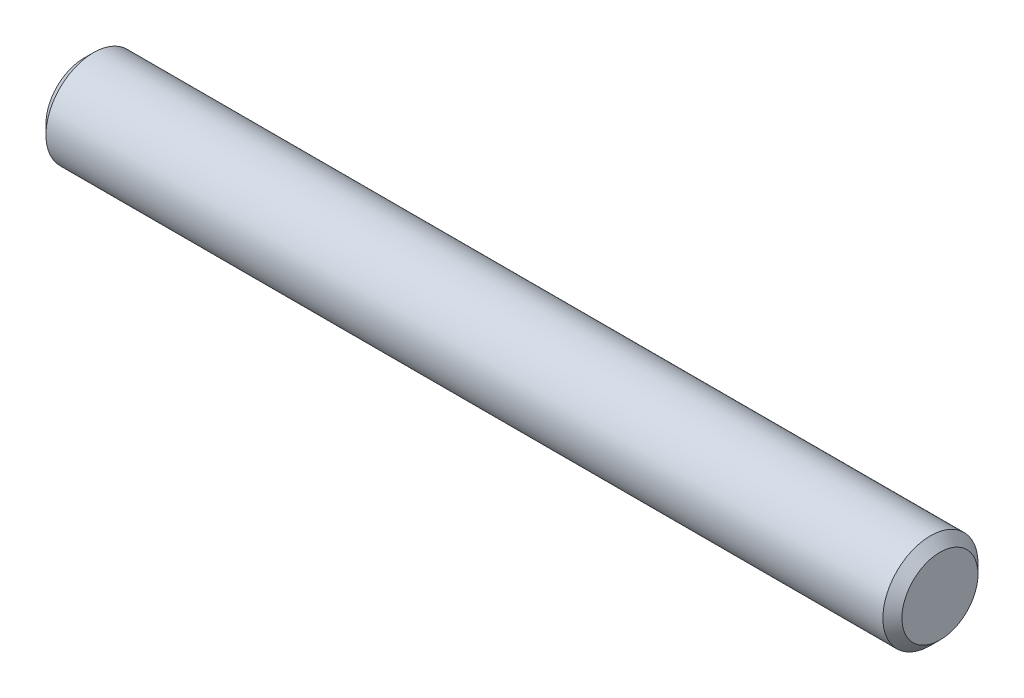
SolidWorks part; units mm, degrees
ref_plane "Front" through (0, 0, 0) normal (0, 0, 1) x (1, 0, 0)
ref_plane "Top" through (0, 0, 0) normal (0, 1, 0) x (1, 0, 0)
ref_plane "Right" through (0, 0, 0) normal (1, 0, 0) x (0, 0, -1)
sketch "Sketch1" plane through (0, 0, 0) normal (0, 0, 1) x (1, 0, 0)
  line L0 (-14.2875, 0) -> (14.2875, 0) construction
  line L1 (14.2875, 1.5875) -> (14.2875, -1.5875) construction
  line L2 (-14.2875, 1.5875) -> (-14.2875, -1.5875) construction
  dimension "Length" = 28.575
  dimension "Diameter" = 3.175
sketch "Sketch2" plane through (0, 0, 0) normal (1, 0, 0) x (0, 0, -1)
  circle A0 centre (0, 0) radius 1.5875
extrude "Extrude1" add sketch "Sketch2" against normal up to vertex (14.2875 mm away) and the other way up to vertex (14.2875 mm away) up to point (-14.2875, 1.5875, 0) other way up to point (14.2875, 1.5875, 0)
chamfer "Chamfer1" distance 0.3175 angle 45 2 edges at (14.2875, 0, -1.5875) (-14.2875, 0, -1.5875)
equation "\"D1@Chamfer1\" = \"Diameter@Sketch1\"*.1"
